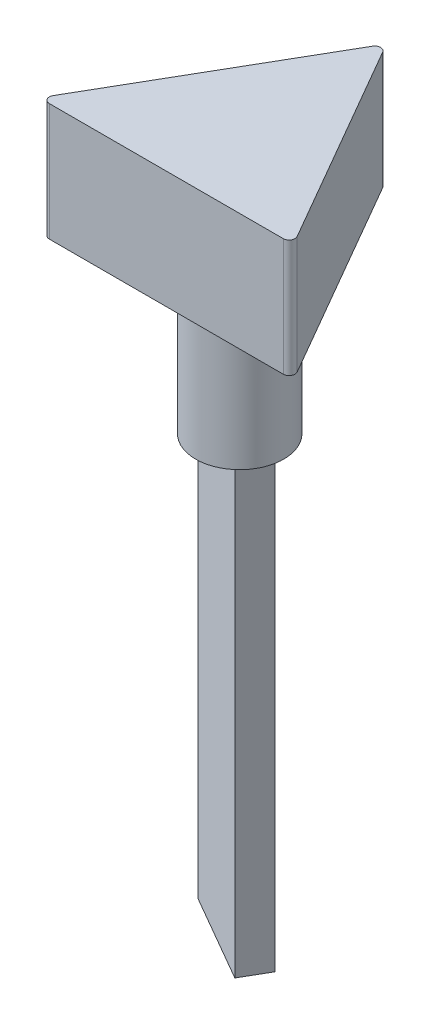
SolidWorks part; units mm, degrees
ref_plane "前视基准面" through (0, 0, 0) normal (0, 0, 1) x (1, 0, 0)
ref_plane "上视基准面" through (0, 0, 0) normal (0, 1, 0) x (1, 0, 0)
ref_plane "右视基准面" through (0, 0, 0) normal (1, 0, 0) x (0, 0, -1)
sketch "草图1" plane through (0, 0, 0) normal (0, 1, 0) x (1, 0, 0)
  line L1 (-0.1732, 4.7) -> (-4.1569, -2.2)
  line L2 (-3.9837, -2.5) -> (3.9837, -2.5)
  line L3 (4.1569, -2.2) -> (0.1732, 4.7)
  circle A0 centre (0, 0) radius 5 construction
  arc A1 (3.9837, -2.5) -> (4.1569, -2.2) centre (3.9837, -2.3) ccw
  arc A2 (-3.9837, -2.5) -> (-4.1569, -2.2) centre (-3.9837, -2.3) cw
  arc A3 (0.1732, 4.7) -> (-0.1732, 4.7) centre (0, 4.6) ccw
  point P12 (0, 5)
  dimension "D1" = 10
  dimension "D2" = 0.2
extrude "凸台-拉伸1" add sketch "草图1" along normal blind 4
sketch "草图2" plane through (0, 0, 0) normal (0, -1, 0) x (1, 0, 0)
  circle A0 centre (0, 0) radius 1.5
  dimension "D1" = 3
extrude "凸台-拉伸2" add sketch "草图2" along normal blind 5
sketch "草图3" plane through (0, -5, 0) normal (0, -1, 0) x (1, 0, 0)
  line L0 (-3.272, -1.8891) -> (-0.7494, -0.4326) construction
  line L1 (-1.9821, -0.567) -> (0.9747, 1.1401)
  line L2 (-1.9821, -0.567) -> (-1.4821, -1.433)
  line L3 (-1.4821, -1.433) -> (1.4747, 0.2741)
  line L4 (0.9747, 1.1401) -> (1.4747, 0.2741)
  line L5 (-0.1732, -4.7) -> (-4.1569, 2.2) construction
  circle A1 centre (0, 0) radius 1.5 construction
  dimension "D1" = 1
  dimension "D2" = 2
extrude "凸台-拉伸3" add sketch "草图3" along normal blind 15
